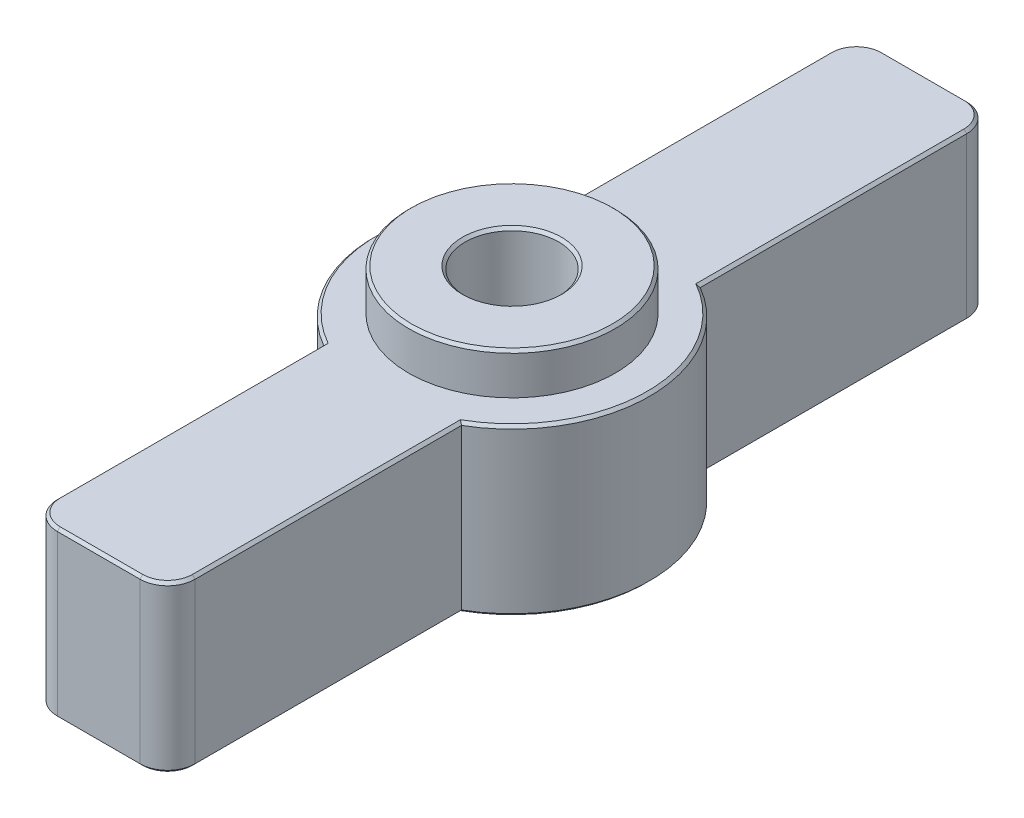
SolidWorks part; units mm, degrees
ref_plane "Front Plane" through (0, 0, 0) normal (0, 0, 1) x (1, 0, 0)
ref_plane "Top Plane" through (0, 0, 0) normal (0, 1, 0) x (1, 0, 0)
ref_plane "Right Plane" through (0, 0, 0) normal (1, 0, 0) x (0, 0, -1)
other "Configuration Table"
sketch "草图1" plane through (0, 0, 0) normal (0, 1, 0) x (1, 0, 0)
  line L0 (-5, 0) -> (5, 0) construction
  line L1 (-5, -28) -> (-5, -8.6603)
  line L2 (5, -28) -> (5, -8.6603)
  line L3 (-3, 30) -> (3, 30)
  line L4 (-3, -30) -> (3, -30)
  line L5 (-5, 8.6603) -> (-5, 28)
  line L6 (5, 8.6603) -> (5, 28)
  arc A0 (-5, 8.6603) -> (-5, -8.6603) centre (0, 0) ccw
  arc A1 (3, -30) -> (5, -28) centre (3, -28) ccw
  arc A2 (-3, -30) -> (-5, -28) centre (-3, -28) cw
  arc A3 (5, 28) -> (3, 30) centre (3, 28) ccw
  arc A4 (-5, 28) -> (-3, 30) centre (-3, 28) cw
  arc A5 (5, -8.6603) -> (5, 8.6603) centre (0, 0) ccw
  point P6 (0, 0)
  point P9 (-5, 0)
  point P12 (5, 0)
  dimension "D1" = 60
  dimension "D2" = 2
  dimension "D3" = 10
extrude "凸台-拉伸1" add sketch "草图1" along normal blind 12
sketch "草图2" plane through (0, 0, 0) normal (0, -1, 0) x (1, 0, 0)
  circle A0 centre (0, 0) radius 6.75
extrude "切除-拉伸1" cut sketch "草图2" against normal blind 8.5
sketch "草图4" plane through (0, 12, 0) normal (0, 1, 0) x (1, 0, 0)
  circle A0 centre (0, 0) radius 7.5
  dimension "D1" = 15
extrude "凸台-拉伸2" add sketch "草图4" along normal blind 3
sketch "草图3" plane through (0, 8.5, 0) normal (0, -1, 0) x (1, 0, 0)
  circle A0 centre (0, 0) radius 3.4
  dimension "D1" = 6.8
extrude "切除-拉伸2" cut sketch "草图3" against normal through all
chamfer "倒角1" distance 0.2 angle 45 27 edges at (5, 12, 18.3301) (4.4142, 12, 29.4142) (0, 12, 30) (-4.4142, 12, 29.4142) (-5, 12, 18.3301) (-10, 12, 0) (0, 15, 7.5) (0, 15, -3.4) (5, 0, -18.3301) (4.4142, 0, -29.4142) (0, 0, -30) (-4.4142, 0, -29.4142) (-5, 0, -18.3301) (-5, 0, 18.3301) (-4.4142, 0, 29.4142) (0, 0, 30) (4.4142, 0, 29.4142) (5, 0, 18.3301) (-10, 0, 0) (0, 0, -6.75) (-5, 12, -18.3301) (-4.4142, 12, -29.4142) (0, 12, -30) (4.4142, 12, -29.4142) (5, 12, -18.3301) (10, 12, 0) (10, 0, 0)
